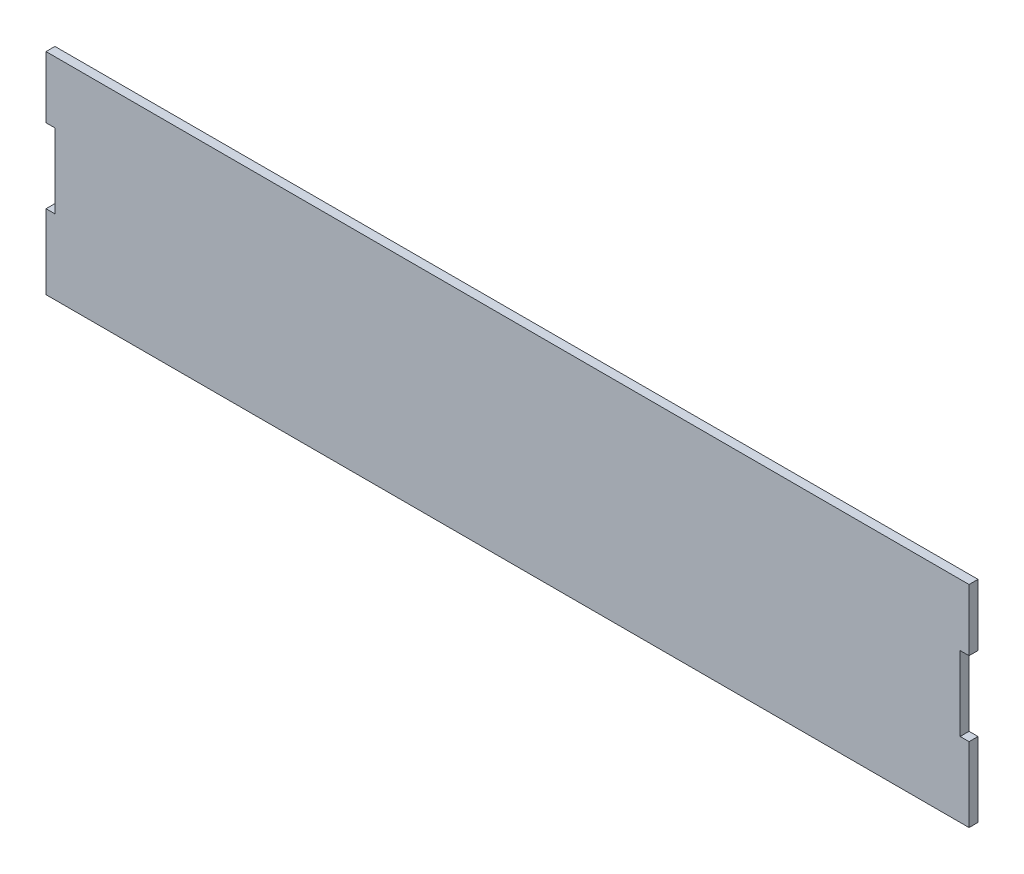
SolidWorks part; units mm, degrees
material "아크릴(내충격성)"
ref_plane "정면" through (0, 0, 0) normal (0, 0, 1) x (1, 0, 0)
ref_plane "윗면" through (0, 0, 0) normal (0, 1, 0) x (1, 0, 0)
ref_plane "우측면" through (0, 0, 0) normal (1, 0, 0) x (0, 0, -1)
sketch "스케치1" plane through (0, 0, 0) normal (0, 0, 1) x (1, 0, 0)
  line L0 (-155, -30.355) -> (155, -30.355) construction
  line L2 (-155, 35.355) -> (-155, 14.645)
  line L4 (155, 35.355) -> (155, 14.645)
  line L5 (-155, 35.355) -> (155, -35.355) construction
  line L6 (-155, -35.355) -> (155, 35.355) construction
  line L15 (-152, 58.5528) -> (-152, -52.5403) construction
  line L16 (-155, 14.645) -> (-152, 14.645)
  line L17 (-152, 14.645) -> (-152, -10.355)
  line L18 (-152, -10.355) -> (-155, -10.355)
  line L19 (-155, -10.355) -> (-155, -35.355)
  line L20 (0, 68.6089) -> (0, -87.8352) construction
  line L21 (152, -10.355) -> (155, -10.355)
  line L22 (152, 14.645) -> (152, -10.355)
  line L23 (155, 14.645) -> (152, 14.645)
  line L24 (155, -10.355) -> (155, -35.355)
  line L25 (-155, 32.355) -> (155, 32.355) construction
  line L29 (-155, 35.355) -> (155, 35.355)
  line L33 (-155, -35.355) -> (155, -35.355)
  point P0 (0, 0)
  dimension "D1" = 310
  dimension "D2" = 25
  dimension "D8" = 3
  dimension "D9" = 25
  dimension "D10" = 20.71
extrude "보스-돌출1" add sketch "스케치1" along normal blind 3
